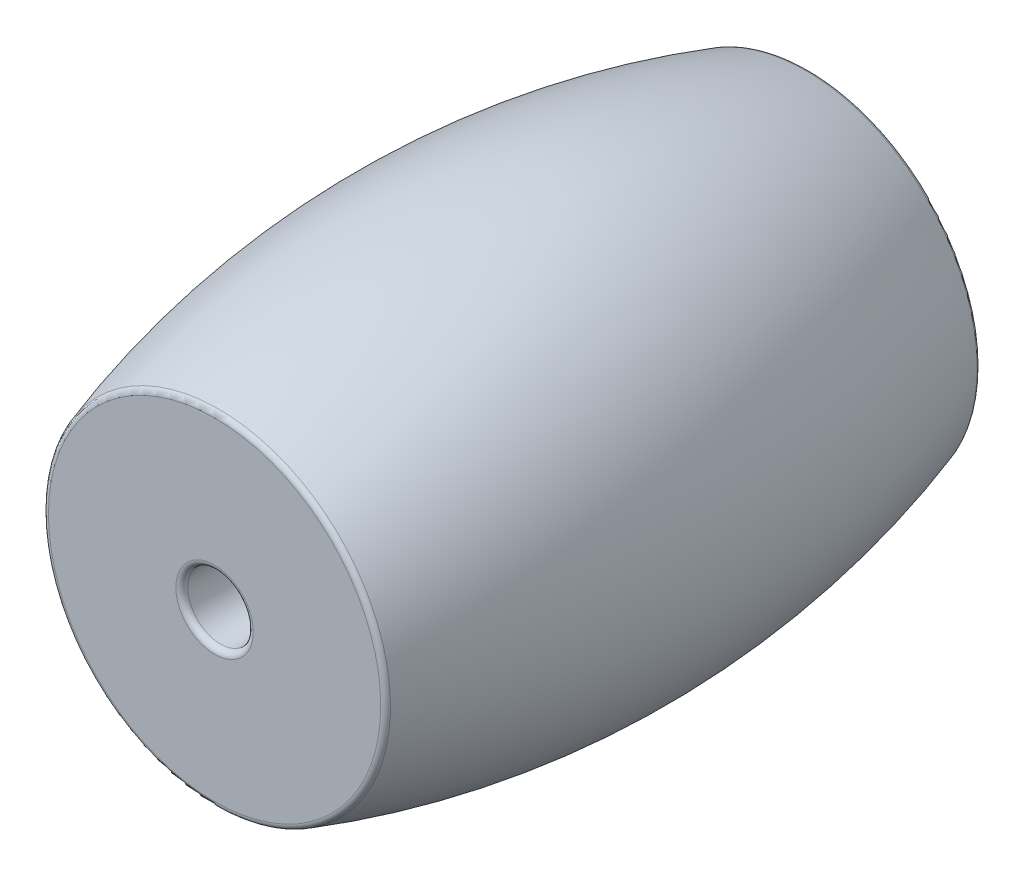
SolidWorks part; units mm, degrees
ref_plane "Ebene vorne" through (0, 0, 0) normal (0, 0, 1) x (1, 0, 0)
ref_plane "Ebene oben" through (0, 0, 0) normal (0, 1, 0) x (1, 0, 0)
ref_plane "Ebene rechts" through (0, 0, 0) normal (1, 0, 0) x (0, 0, -1)
sketch "Skizze1" plane through (0, 0, 0) normal (1, 0, 0) x (0, 0, -1)
  line L0 (-31.773, 0) -> (28.8618, 0)
  line L1 (-15, 16.65) -> (15, 16.65)
  line L2 (-15, 16.65) -> (-15, 1.65)
  line L3 (-15, 1.65) -> (15, 1.65)
  line L4 (15, 16.65) -> (15, 1.65)
  circle A0 centre (0, -37) radius 48
  dimension "D1" = 30
  dimension "D5" = 96
  dimension "D2" = 15
  dimension "D3" = 1.65
  dimension "D4" = 37
ref_axis "Achse1" through (0, 0, 31.773) along (0, 0, -1)
revolve "Rotation3" add sketch "Skizze1" angle 360 about axis through (0, 0, 31.773) along (0, 0, -1)
fillet "Verrundung1" radius 0.3 4 edges at (1.65, 0, 15) (1.65, 0, -15) (8.5961, 0, -15) (8.5961, 0, 15)
